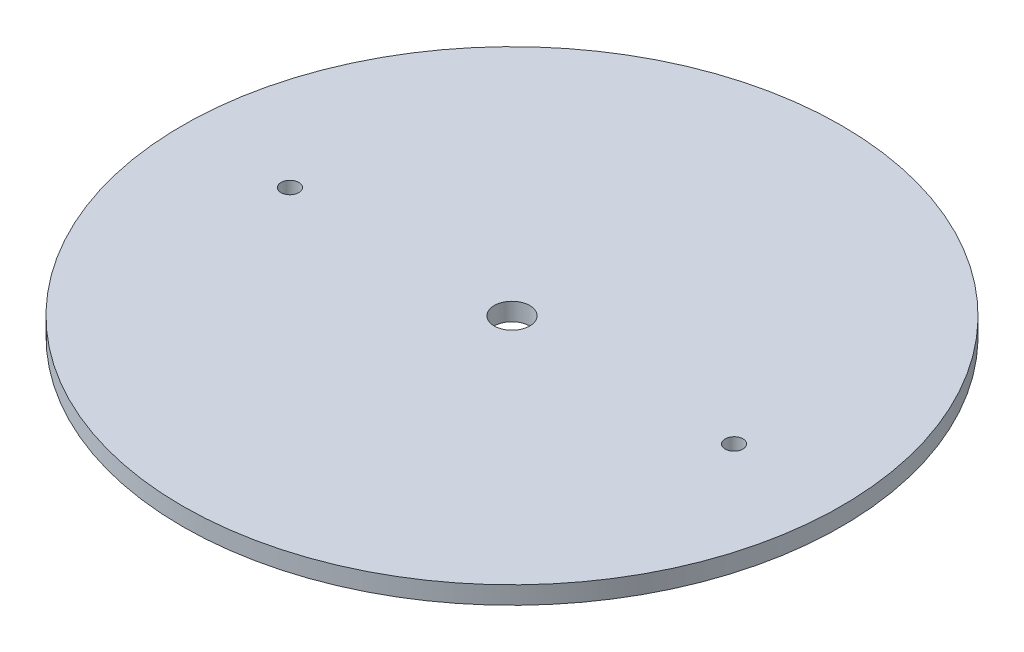
SolidWorks part; units mm, degrees
ref_plane "Front Plane" through (0, 0, 0) normal (0, 0, 1) x (1, 0, 0)
ref_plane "Top Plane" through (0, 0, 0) normal (0, 1, 0) x (1, 0, 0)
ref_plane "Right Plane" through (0, 0, 0) normal (1, 0, 0) x (0, 0, -1)
sketch "Sketch1" plane through (0, 0, 0) normal (0, 1, 0) x (1, 0, 0)
  line L0 (0, 0) -> (-50, 0) construction
  line L1 (0, 0) -> (0, -18.6216) construction
  circle A0 centre (0, 0) radius 74.2
  circle A1 centre (0, 0) radius 4
  circle A2 centre (-50, 0) radius 2
  circle A3 centre (50, 0) radius 2
  dimension "D1" = 8
  dimension "D2" = 148.4
  dimension "D3" = 4
  dimension "D4" = 50
extrude "Boss-Extrude1" add sketch "Sketch1" along normal blind 4
